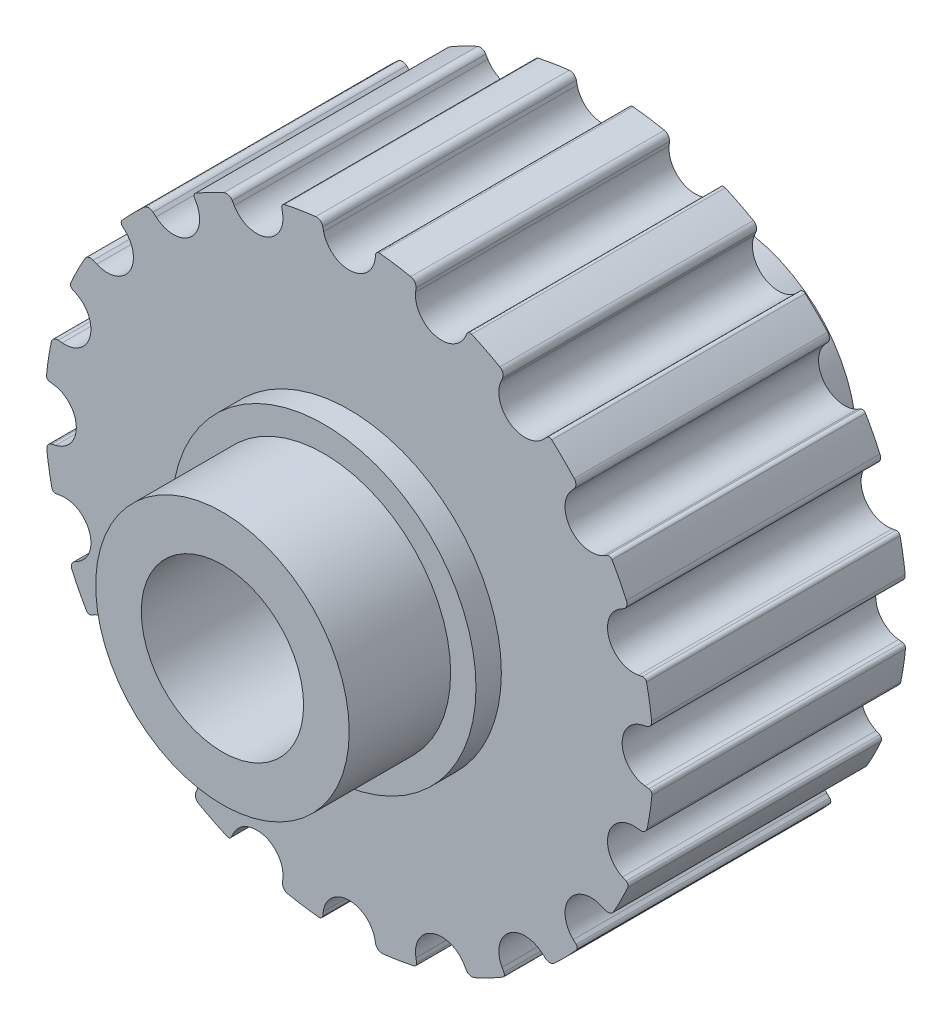
SolidWorks part; units mm, degrees
ref_plane "前视基准面" through (0, 0, 0) normal (0, 0, 1) x (1, 0, 0)
ref_plane "上视基准面" through (0, 0, 0) normal (0, 1, 0) x (1, 0, 0)
ref_plane "右视基准面" through (0, 0, 0) normal (1, 0, 0) x (0, 0, -1)
sketch "草图1" plane through (0, 0, 0) normal (0, 0, 1) x (1, 0, 0)
  circle A0 centre (0, 0) radius 6
  circle A1 centre (0, 0) radius 2.5
  dimension "D1" = 12
  dimension "D2" = 5
extrude "凸台-拉伸1" add sketch "草图1" along normal blind 5
sketch "草图2" plane through (0, 0, 5) normal (0, 0, 1) x (1, 0, 0)
  line L0 (0.5217, 5.909) -> (0.5119, 5.8324)
  line L3 (-0.5208, 5.8626) -> (-0.5038, 5.7859)
  arc A0 (-0.5038, 5.7859) -> (0.5119, 5.8324) centre (0, 5.8977) ccw
  arc A2 (0.5217, 5.909) -> (0.5984, 5.9701) centre (0.5914, 5.9001) cw
  arc A5 (-0.5208, 5.8626) -> (-0.6617, 5.9634) centre (-0.6474, 5.8345) ccw
  circle A8 centre (0, 0) radius 6 construction
  circle A10 centre (0, 0) radius 6
  circle M1 centre (0, 0) radius 6
  dimension "D1" = 0.0767
  dimension "D2" = 0.0767
extrude "切除-拉伸1" cut sketch "草图2" against normal blind 5 contours A5 L3 A0 L0 A2 M1
pattern_circular "阵列(圆周)1" count 20 over 360 about axis through (0, 0, 0) along (0, 0, 1) of "切除-拉伸1"
sketch "草图3" plane through (0, 0, 5) normal (0, 0, 1) x (1, 0, 0)
  circle A0 centre (0, 0) radius 3
  circle A1 centre (0, 0) radius 2.5
  dimension "D1" = 0.5
extrude "凸台-拉伸2" add sketch "草图3" against normal offset from surface (6 mm away) 0.5 from offset 0.5
sketch "草图4" plane through (0, 0, -0.5) normal (0, 0, -1) x (-1, 0, 0)
  circle A0 centre (0, 0) radius 2.5
  circle A1 centre (0, 0) radius 1.6
  dimension "D1" = 3.2
  dimension "D2" = 5
extrude "凸台-拉伸3" add sketch "草图4" along normal blind 2 separate body
sketch "草图5" plane through (0, 0, -0.5) normal (0, 0, 1) x (1, 0, 0)
  circle A0 centre (0, 0) radius 1.6 construction
  circle A1 centre (0, 0) radius 2.5
  circle A2 centre (0, 0) radius 2.5
  circle A3 centre (0, 0) radius 1.6
  dimension "D1" = 0
extrude "凸台-拉伸4" add sketch "草图5" along normal offset from surface (8 mm away) 2 up to face at (2.5, 0, 5.5) offset beyond the face yes
